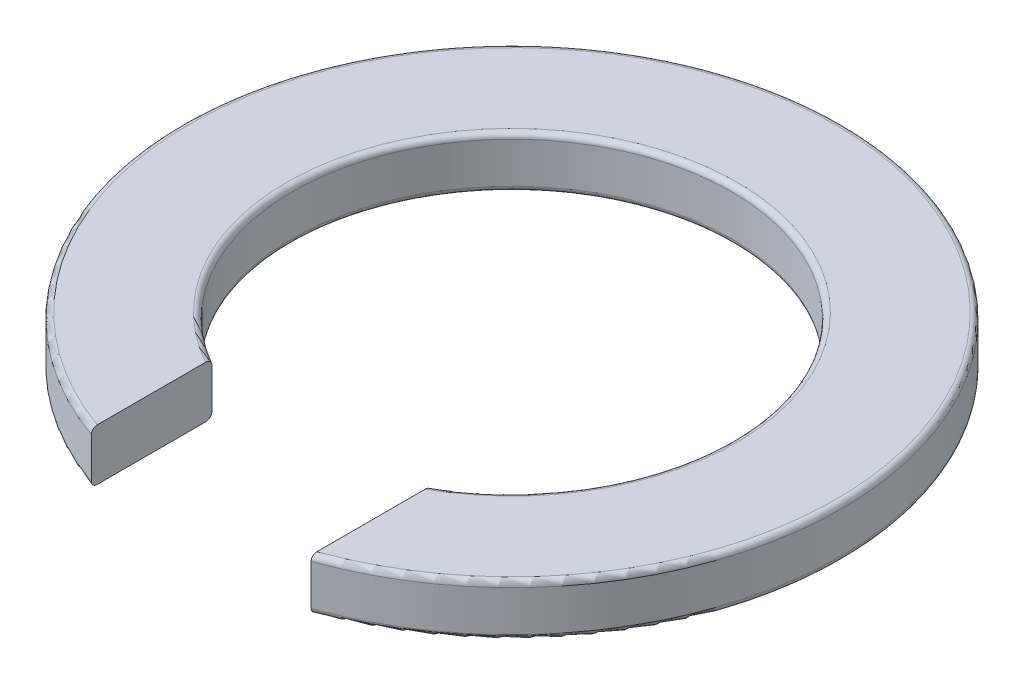
SolidWorks part; units mm, degrees
ref_plane "Front Plane" through (0, 0, 0) normal (0, 0, 1) x (1, 0, 0)
ref_plane "Top Plane" through (0, 0, 0) normal (0, 1, 0) x (1, 0, 0)
ref_plane "Right Plane" through (0, 0, 0) normal (1, 0, 0) x (0, 0, -1)
sketch "Sketch1" plane through (0, 0, 0) normal (0, 1, 0) x (1, 0, 0)
  circle A0 centre (0, 0) radius 30
  circle A1 centre (0, 0) radius 20
  dimension "D1" = 60
  dimension "D2" = 10
extrude "Boss-Extrude1" add sketch "Sketch1" along normal blind 4.7
fillet "Fillet1" radius 0.5 4 edges at (0, 0, 20) (0, 4.7, 20) (0, 0, 30) (0, 4.7, 30)
sketch "Sketch2" plane through (0, 4.7, 0) normal (0, 1, 0) x (1, 0, 0)
  line L0 (0, -17.3205) -> (0, 0) construction
  line L1 (-10, -17.3205) -> (10, -17.3205)
  line L2 (-10, -17.3205) -> (-10, -30)
  line L3 (-10, -30) -> (10, -30)
  line L4 (10, -17.3205) -> (10, -30)
  circle A0 centre (0, 0) radius 20 construction
  circle A1 centre (0, 0) radius 30 construction
  dimension "D1" = 20
extrude "Cut-Extrude1" cut sketch "Sketch2" against normal through all
